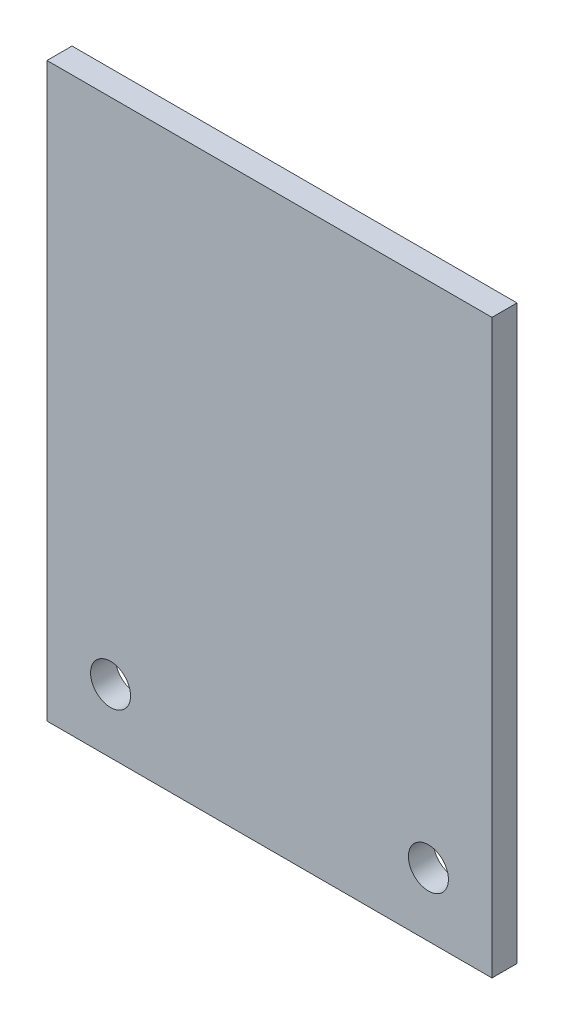
SolidWorks part; units mm, degrees
ref_plane "Front Plane" through (0, 0, 0) normal (1, 0, 0) x (0, 1, 0)
ref_plane "Top Plane" through (0, 0, 0) normal (0, 0, 1) x (0, 1, 0)
ref_plane "Right Plane" through (0, 0, 0) normal (0, 1, 0) x (-1, 0, 0)
sketch "Sketch1" plane through (0, 0, 0) normal (0, 0, 1) x (0, 1, 0)
  line L0 (-30.0816, 0) -> (10306.2778, 0) construction
  line L1 (-17.145, 13.335) -> (17.145, 13.335)
  line L2 (-17.145, 13.335) -> (-17.145, -13.335)
  line L3 (-17.145, -13.335) -> (17.145, -13.335)
  line L4 (17.145, 13.335) -> (17.145, -13.335)
  line L5 (-17.145, 13.335) -> (17.145, -13.335) construction
  line L6 (-17.145, -13.335) -> (17.145, 13.335) construction
  circle A0 centre (-13.335, 9.525) radius 1.2
  circle A1 centre (-13.335, -9.525) radius 1.2
  point P0 (0, 0)
  point P10 (-17.145, 0)
  dimension "D5" = 2.4
  dimension "D1" = 9.525
  dimension "D2" = 3.81
  dimension "D3" = 34.29
  dimension "D4" = 26.67
extrude "Boss-Extrude1" add sketch "Sketch1" along normal blind 1.5
